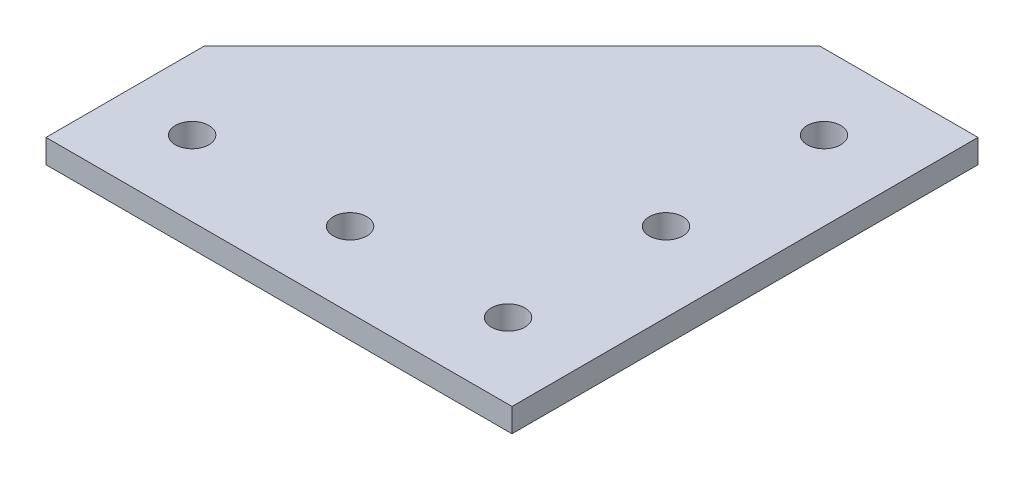
SolidWorks part; units mm, degrees
ref_plane "前视基准面" through (0, 0, 0) normal (0, 0, 1) x (1, 0, 0)
ref_plane "上视基准面" through (0, 0, 0) normal (0, 1, 0) x (1, 0, 0)
ref_plane "右视基准面" through (0, 0, 0) normal (1, 0, 0) x (0, 0, -1)
sketch "草图1" plane through (0, 0, 0) normal (0, 1, 0) x (1, 0, 0)
  line L0 (28.1883, 27.6427) -> (146.1883, 27.6427)
  line L1 (146.1883, 27.6427) -> (146.1883, 145.6427)
  line L2 (146.1883, 145.6427) -> (106.1883, 145.6427)
  line L3 (28.1883, 27.6427) -> (28.1883, 67.6427)
  line L4 (28.1883, 67.6427) -> (106.1883, 145.6427)
  circle A0 centre (126.1883, 126.6427) radius 4.25
  circle A1 centre (126.1883, 86.6427) radius 4.25
  circle A2 centre (126.1883, 46.6427) radius 4.25
  circle A3 centre (86.1883, 46.6427) radius 4.25
  circle A4 centre (46.1883, 46.6427) radius 4.25
extrude "凸台-拉伸1" add sketch "草图1" along normal blind 6
